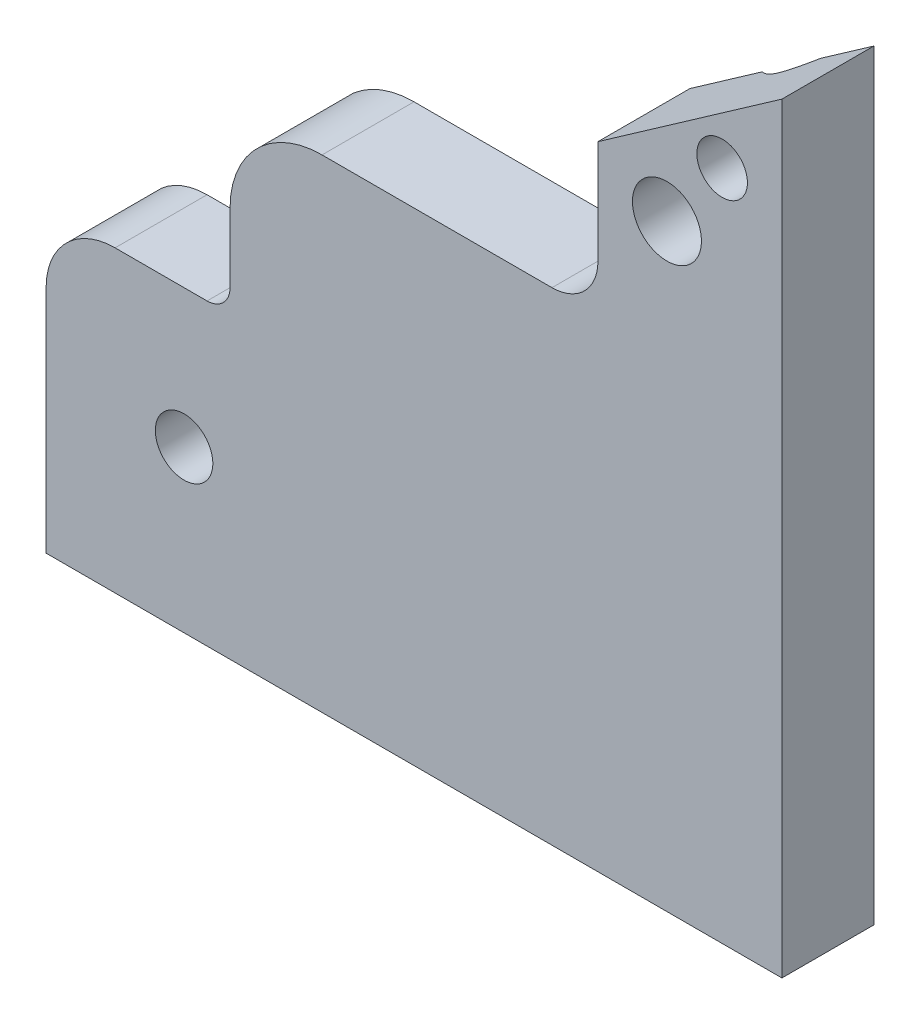
SolidWorks part; units mm, degrees
material "6061 Alloy"
ref_plane "Front Plane" through (0, 0, 0) normal (0, 0, 1) x (1, 0, 0)
ref_plane "Top Plane" through (0, 0, 0) normal (0, 1, 0) x (1, 0, 0)
ref_plane "Right Plane" through (0, 0, 0) normal (1, 0, 0) x (0, 0, -1)
ref_plane "Plane1" through (0, 0, 4) normal (0, 0, 1) x (1, 0, 0)
sketch "Sketch1" plane through (0, 0, 4) normal (0, 0, 1) x (1, 0, 0)
  line L0 (32, 25.5) -> (0, 25.5)
  line L1 (0, 25.5) -> (0, -2)
  line L2 (0, -2) -> (32, -2)
  line L3 (32, -2) -> (32, 25.5)
  dimension "D1" = 32
  dimension "D2" = 27.5
extrude "Boss-Extrude1" add sketch "Sketch1" against normal blind 4
sketch "Sketch2" plane through (0, 0, 0) normal (0, 0, -1) x (-1, 0, 0)
  line L0 (-8, 25.5) -> (-8, 11)
  line L1 (-8, 11) -> (0, 11)
  line L2 (0, 11) -> (0, 25.5)
  line L3 (0, 25.5) -> (-8, 25.5)
  line L4 (-32, 25.5) -> (0, 25.5) construction
  dimension "D1" = 14.5
  dimension "D2" = 0
extrude "Cut-Extrude1" cut sketch "Sketch2" against normal through all
sketch "Sketch3" plane through (0, 0, 0) normal (0, 0, -1) x (-1, 0, 0)
  line L0 (-24, 25.5) -> (-24, 19)
  line L1 (-24, 19) -> (-8, 19)
  line L2 (-8, 19) -> (-8, 25.5)
  line L3 (-8, 25.5) -> (-24, 25.5)
extrude "Cut-Extrude2" cut sketch "Sketch3" against normal through all
draft "Draft1" type of draft neutral plane draft angle 35 faces to draft 1 face at (28, 25.5, 2) neutral plane through (24, 25.5, 4) neutral plane normal (-1, 0, 0) parameters "D1"=35
ref_plane "Plane2" through (0, 5, 0) normal (0, 1, 0) x (1, 0, 0)
sketch "Sketch4" plane through (0, 5, 0) normal (0, 1, 0) x (1, 0, 0)
  line L0 (8, 5) -> (6, 5)
  line L1 (6, 5) -> (6, 0)
  line L2 (6, 0) -> (8, 0)
  line L3 (8, 0) -> (8, 5)
  line L4 (6, 5) -> (6, 0) construction
ref_plane "Plane3" through (0, 14, 0) normal (0, -1, 0) x (1, 0, 0)
hole_wizard "Ø3.0 (3) Diameter Hole1" positions "Sketch9" profile "Sketch8" hole size "Ø3.0" standard "ANSI Metric" end condition through all
sketch "Sketch9" plane through (0, 0, 0) normal (0, 0, -1) x (-1, 0, 0)
  line L0 (-24, 25.5) -> (-24, 19) construction
  point P0 (-27, 24)
  dimension "D1" = 3
  dimension "D2" = 1.5
sketch "Sketch8" plane through (27, 24, 0) normal (1, 0, 0) x (0, 1, 0)
  line L0 (0, 0) -> (0, 4)
  line L1 (0, 4) -> (1.5, 4)
  line L2 (1.5, 4) -> (1.5, 0)
  line L5 (1.5, 0) -> (0, 0)
  line L11 (0, -6.35) -> (0, 107.95) construction
  dimension "Thru Hole Dia." = 3
  dimension "Thru Hole Depth" = 4
hole_wizard "CSK for M3 SFHCS1" positions "Sketch11" profile "Sketch10" countersink size "M3" standard "ANSI Metric"
sketch "Sketch11" plane through (0, 0, 0) normal (0, 0, -1) x (-1, 0, 0)
  line L0 (-32, -2) -> (-32, 31.1017) construction
  point P0 (-29.4, 27.2)
  dimension "D1" = 2.6
  dimension "D2" = 1.7
sketch "Sketch10" plane through (29.4, 27.2, 0) normal (1, 0, 0) x (0, 1, 0)
  line L0 (0, 0) -> (0, 10.1609)
  line L1 (0, 10.1609) -> (1.1, 9.5)
  line L2 (1.1, 9.5) -> (1.1, 1.2)
  line L3 (1.1, 1.2) -> (2.3, 0)
  line L5 (2.3, 0) -> (0, 0)
  line L6 (-1.1, 1.2) -> (-2.3, 0) construction
  line L10 (0, 10.1609) -> (-1.1, 9.5) construction
  line L11 (0, -6.35) -> (0, 107.95) construction
  dimension "Hole Dia." = 2.2
  dimension "Hole Depth" = 9.5
  dimension "Near C'Sink Dia." = 4.6
  dimension "Near C'Sink Angle" = 90
  dimension "Drill Angle" = 118
hole_wizard "M3x0.5 Tapped Hole2" positions "Sketch13" profile "Sketch12" tap size "M3x0.5" standard "ANSI Metric"
sketch "Sketch13" plane through (0, -2, 0) normal (0, -1, 0) x (-1, 0, 0)
  point P0 (-10, -2)
  point P1 (-19.5, -2)
  point P2 (-29, -2)
sketch "Sketch12" plane through (10, -2, 2) normal (1, 0, 0) x (0, 0, -1)
  line L0 (0, 0) -> (0, 8.2511)
  line L1 (0, 8.2511) -> (1.25, 7.5)
  line L2 (1.25, 7.5) -> (1.25, 0)
  line L5 (1.25, 0) -> (0, 0)
  line L10 (0, 8.2511) -> (-1.25, 7.5) construction
  line L11 (0, -6.35) -> (0, 107.95) construction
  dimension "Tap Drill Dia." = 2.5
  dimension "Tap Drill Depth" = 7.5
  dimension "Drill Angle" = 118
fillet "Fillet1" radius 1 1 edges at (8, 11, 2)
fillet "Fillet2" radius 2 1 edges at (24, 19, 2)
fillet "Fillet3" radius 3 1 edges at (0, 11, 2)
fillet "Fillet4" radius 4 1 edges at (8, 19, 2)
hole_wizard "M3x0.5 Tapped Hole1" positions "3DSketch1" profile "Sketch14" tap size "M3x0.5" standard "ANSI Metric" end condition through all
sketch3d "3DSketch1"
  line L0 (0, 8, 0) -> (0, -2, 0) construction
  line L1 (0, -2, 0) -> (32, -2, 0) construction
  point P0 (6, 5, 0)
  dimension "D1" = 6
  dimension "D2" = 7
sketch "Sketch14" plane through (6, 5, 0) normal (1, 0, 0) x (0, 1, 0)
  line L0 (0, 0) -> (0, 4)
  line L1 (0, 4) -> (1.25, 4)
  line L2 (1.25, 4) -> (1.25, 0)
  line L5 (1.25, 0) -> (0, 0)
  line L11 (0, -6.35) -> (0, 107.95) construction
  dimension "Thread Major Dia." = 2.5
  dimension "Thru Tap Drill Depth" = 4
